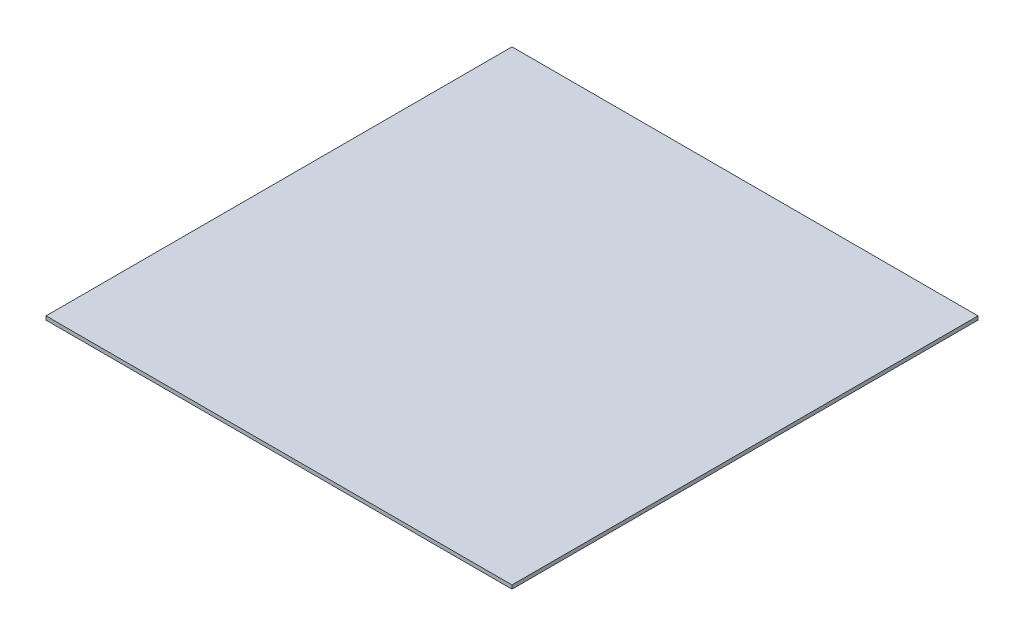
SolidWorks part; units mm, degrees
ref_plane "Front Plane" through (0, 0, 0) normal (0, 0, 1) x (1, 0, 0)
ref_plane "Top Plane" through (0, 0, 0) normal (0, 1, 0) x (1, 0, 0)
ref_plane "Right Plane" through (0, 0, 0) normal (1, 0, 0) x (0, 0, -1)
sketch "Sketch1" plane through (0, 0, 0) normal (0, 1, 0) x (1, 0, 0)
  line L1 (0, 0) -> (400, 0)
  line L2 (0, 0) -> (0, 400)
  line L3 (0, 400) -> (400, 400)
  line L4 (400, 0) -> (400, 400)
  dimension "D1" = 400
extrude "Boss-Extrude1" add sketch "Sketch1" along normal blind 3.175
